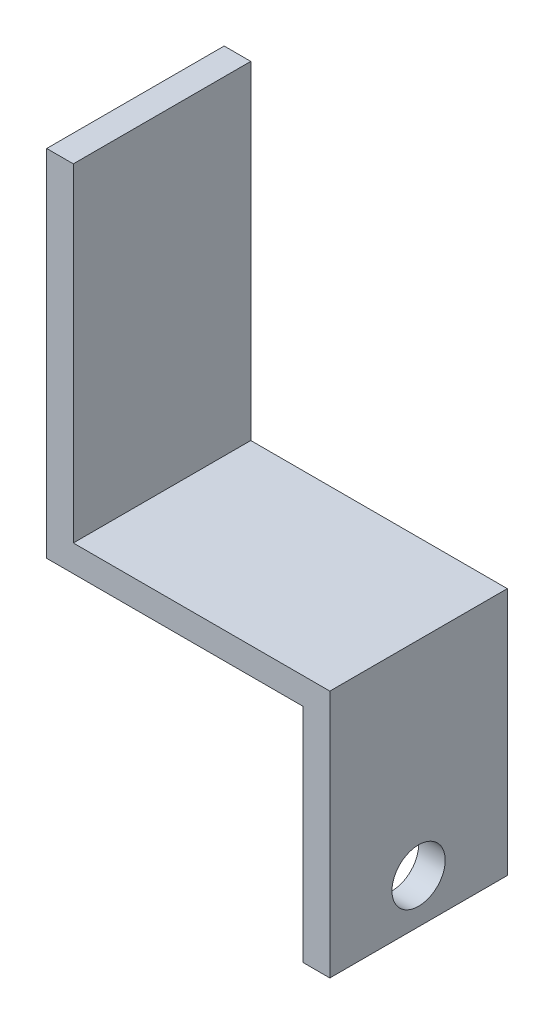
SolidWorks part; units mm, degrees
ref_plane "Front Plane" through (0, 0, 0) normal (0, 0, 1) x (1, 0, 0)
ref_plane "Top Plane" through (0, 0, 0) normal (0, 1, 0) x (1, 0, 0)
ref_plane "Right Plane" through (0, 0, 0) normal (1, 0, 0) x (0, 0, -1)
sketch "Sketch1" plane through (0, 0, 0) normal (0, 0, 1) x (1, 0, 0)
  line L6 (0, 0) -> (0, -27.999)
  line L7 (-3, -2.999) -> (-3, -27.999)
  line L8 (0, -27.999) -> (-3, -27.999)
  line L10 (-3, -2.999) -> (-31.9076, -2.999)
  line L11 (-31.9076, -2.999) -> (-31.9076, 37.001)
  line L13 (-28.9076, 0) -> (-28.9076, 37.001)
  line L14 (-28.9076, 37.001) -> (-31.9076, 37.001)
  line L16 (0, 0) -> (-2.9244, 0) construction
  line L17 (-3, -2.999) -> (-3, -2.999) construction
  line L18 (-28.9076, 0) -> (0, 0)
  dimension "D1" = 3
  dimension "D2" = 2.999
  dimension "D3" = 25
  dimension "D4" = 40
  dimension "D5" = 28.9076
  dimension "D6" = 3
extrude "Boss-Extrude1" add sketch "Sketch1" along normal blind 20
sketch "Sketch3" plane through (0, 0, 0) normal (1, 0, 0) x (0, 0, -1)
  line L6 (0, -27.999) -> (0, 0) construction
  line L7 (-20, -27.999) -> (0, -27.999) construction
  circle A0 centre (-10, -22.999) radius 3
  point P0 (-11.8871, -30.429)
  dimension "D1" = 6
  dimension "D2" = 5
  dimension "D3" = 10
extrude "Cut-Extrude2" cut sketch "Sketch3" against normal blind 3
